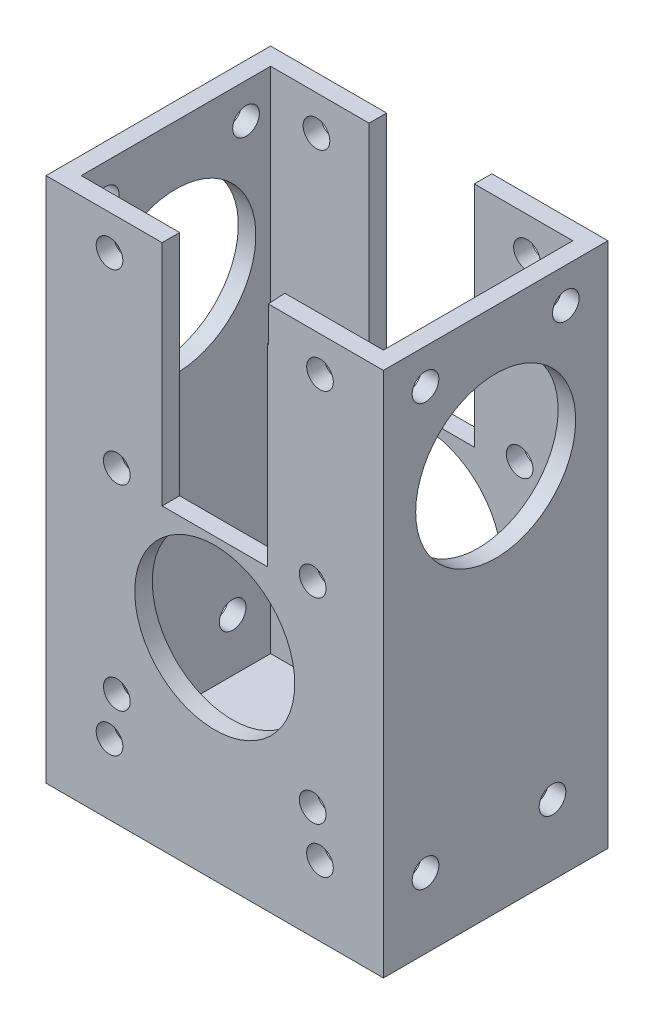
SolidWorks part; units mm, degrees
ref_plane "Front Plane" through (0, 0, 0) normal (0, 0, 1) x (1, 0, 0)
ref_plane "Top Plane" through (0, 0, 0) normal (0, 1, 0) x (1, 0, 0)
ref_plane "Right Plane" through (0, 0, 0) normal (1, 0, 0) x (0, 0, -1)
sketch "Sketch1" plane through (0, 0, 0) normal (0, 1, 0) x (1, 0, 0)
  line L1 (0, 0) -> (61.0616, 0)
  line L2 (0, 0) -> (0, 40.64)
  line L3 (0, 40.64) -> (61.0616, 40.64)
  line L4 (61.0616, 0) -> (61.0616, 40.64)
  dimension "D1" = 61.0616
  dimension "D2" = 40.64
extrude "Boss-Extrude1" add sketch "Sketch1" along normal blind 82.55
sketch "Sketch13" plane through (0, 82.55, 0) normal (0, 1, 0) x (1, 0, 0)
  line L1 (3.175, 3.175) -> (57.8866, 3.175)
  line L2 (3.175, 3.175) -> (3.175, 37.465)
  line L3 (3.175, 37.465) -> (57.8866, 37.465)
  line L4 (57.8866, 3.175) -> (57.8866, 37.465)
  dimension "D1" = 54.7116
  dimension "D2" = 34.29
extrude "Cut-Extrude1" cut sketch "Sketch13" against normal blind 82.55
sketch "Sketch15" plane through (0, 0, 0) normal (0, 0, 1) x (1, 0, 0)
  line L0 (0, 0) -> (61.0616, 0) construction
  circle A0 centre (30.5308, 31.75) radius 14.478
  dimension "D1" = 30.5308
  dimension "D2" = 31.75
extrude "Cut-Extrude2" cut sketch "Sketch15" against normal blind 3.175
sketch "Sketch16" plane through (0, 0, 0) normal (0, 0, 1) x (1, 0, 0)
  circle A0 centre (30.5308, 31.75) radius 14.478
extrude "Cut-Extrude3" cut sketch "Sketch16" against normal blind 3.175 from surface at -37.465 starting at face at (30.5308, 41.275, -37.465)
sketch "Sketch18" plane through (0, 0, 0) normal (-1, 0, 0) x (0, 0, 1)
  line L0 (-40.64, 0) -> (0, 0) construction
  line L1 (0, 82.55) -> (0, 0) construction
  circle A0 centre (-20.32, 63.754) radius 14.478
  dimension "D1" = 63.754
  dimension "D2" = 20.32
extrude "Cut-Extrude4" cut sketch "Sketch18" against normal up to vertex
sketch "Sketch19" plane through (0, 0, -40.64) normal (0, 0, -1) x (-1, 0, 0)
  line L0 (-61.0616, 82.55) -> (0, 82.55) construction
  line L1 (-40.0558, 82.55) -> (-21.0058, 82.55)
  line L2 (-40.0558, 82.55) -> (-40.0558, 47.625)
  line L3 (-40.0558, 47.625) -> (-21.0058, 47.625)
  line L4 (-21.0058, 82.55) -> (-21.0058, 47.625)
  line L5 (0, 82.55) -> (0, 0) construction
  line L6 (-61.0616, 82.55) -> (-61.0616, 0) construction
  dimension "D1" = 19.05
  dimension "D2" = 34.925
  dimension "D3" = 21.0058
  dimension "D4" = 21.0058
extrude "Cut-Extrude5" cut sketch "Sketch19" against normal up to vertex
sketch "Sketch20" plane through (0, 0, 0) normal (0, 0, 1) x (1, 0, 0)
  circle A0 centre (48.26, 14.0208) radius 2.413
  circle A1 centre (30.5308, 31.75) radius 14.478 construction
  dimension "D1" = 17.7292
  dimension "D2" = 17.7292
sketch "Sketch21" plane through (0, 0, 0) normal (0, 0, 1) x (1, 0, 0)
  circle A0 centre (48.26, 49.4737) radius 2.413
sketch "Sketch24" plane through (0, 0, 0) normal (0, 0, 1) x (1, 0, 0)
  circle A0 centre (12.8071, 49.4737) radius 2.413
sketch "Sketch25" plane through (0, 0, 0) normal (0, 0, 1) x (1, 0, 0)
  circle A0 centre (12.8071, 14.0208) radius 2.413
extrude "Cut-Extrude6" cut sketch "Sketch20" against normal up to vertex
extrude "Cut-Extrude7" cut sketch "Sketch21" against normal up to vertex
extrude "Cut-Extrude8" cut sketch "Sketch24" against normal up to vertex contours A0
extrude "Cut-Extrude9" cut sketch "Sketch25" against normal up to vertex contours A0
sketch "Sketch45" plane through (0, 0, 0) normal (0, 0, 1) x (1, 0, 0)
  line L0 (61.0616, 82.55) -> (61.0616, 0) construction
  line L1 (0, 0) -> (61.0616, 0) construction
  circle A0 centre (49.5808, 6.35) radius 2.413
  dimension "D1" = 11.4808
  dimension "D2" = 6.35
sketch "Sketch47" plane through (0, 82.55, 0) normal (0, 1, 0) x (1, 0, 0)
  line L0 (21.0058, 40.64) -> (21.0058, 37.465)
  line L1 (21.0058, 37.465) -> (3.175, 37.465)
  line L2 (3.175, 37.465) -> (3.175, 3.175)
  line L3 (3.175, 3.175) -> (21.0058, 3.175)
  line L4 (21.0058, 3.175) -> (21.0058, 0)
  line L5 (21.0058, 0) -> (0, 0)
  line L6 (0, 0) -> (0, 40.64)
  line L7 (0, 40.64) -> (20.2485, 40.64)
  line L8 (21.0058, 40.64) -> (0, 40.64) construction
  line L9 (20.2485, 40.64) -> (21.0058, 40.64)
extrude "Boss-Extrude2" add sketch "Sketch47" along normal blind 6.35
sketch "Sketch49" plane through (0, 82.55, 0) normal (0, 1, 0) x (1, 0, 0)
  line L0 (40.0558, 37.465) -> (40.0558, 40.64)
  line L1 (40.0558, 40.64) -> (61.0616, 40.64)
  line L2 (61.0616, 40.64) -> (61.0616, 0)
  line L3 (61.0616, 0) -> (40.2245, 0)
  line L4 (40.2245, 0) -> (40.0558, 3.175)
  line L5 (40.0558, 3.175) -> (57.8866, 3.175)
  line L6 (57.8866, 3.175) -> (57.8866, 37.465)
  line L7 (57.8866, 37.465) -> (40.0558, 37.465)
extrude "Boss-Extrude3" add sketch "Sketch49" along normal blind 6.35
sketch "Sketch53" plane through (0, 0, 0) normal (0, -1, 0) x (1, 0, 0)
  line L1 (0, 0) -> (61.0616, 0)
  line L2 (0, 0) -> (0, -40.64)
  line L3 (0, -40.64) -> (61.0616, -40.64)
  line L4 (61.0616, 0) -> (61.0616, -40.64)
  line L5 (3.175, -3.175) -> (57.8866, -3.175)
  line L6 (3.175, -3.175) -> (3.175, -37.465)
  line L7 (3.175, -37.465) -> (57.8866, -37.465)
  line L8 (57.8866, -3.175) -> (57.8866, -37.465)
extrude "Boss-Extrude5" add sketch "Sketch53" along normal blind 3.175
sketch "Sketch54" plane through (0, -3.175, 0) normal (0, -1, 0) x (1, 0, 0)
  line L1 (0, 0) -> (61.0616, 0)
  line L2 (0, 0) -> (0, -40.64)
  line L3 (0, -40.64) -> (61.0616, -40.64)
  line L4 (61.0616, 0) -> (61.0616, -40.64)
extrude "Boss-Extrude6" add sketch "Sketch54" along normal blind 3.175
extrude "Cut-Extrude14" cut sketch "Sketch45" against normal up to vertex
sketch "Sketch59" plane through (0, 0, 0) normal (0, 0, 1) x (1, 0, 0)
  circle A0 centre (49.5808, 82.55) radius 2.413
  circle A1 centre (49.5808, 6.35) radius 2.413 construction
  dimension "D1" = 76.2
extrude "Cut-Extrude18" cut sketch "Sketch59" against normal up to vertex contours A0
sketch "Sketch60" plane through (0, 0, 0) normal (0, 0, 1) x (1, 0, 0)
  circle A0 centre (11.4808, 6.35) radius 2.413
  circle A1 centre (49.5808, 6.35) radius 2.413 construction
  dimension "D1" = 38.1
extrude "Cut-Extrude19" cut sketch "Sketch60" against normal up to vertex
sketch "Sketch61" plane through (0, 0, 0) normal (0, 0, 1) x (1, 0, 0)
  circle A0 centre (11.4808, 82.55) radius 2.413
extrude "Cut-Extrude20" cut sketch "Sketch61" against normal up to vertex
sketch "Sketch63" plane through (0, 0, 0) normal (-1, 0, 0) x (0, 0, 1)
  line L0 (-40.64, 88.9) -> (-40.64, -6.35) construction
  line L1 (-40.64, 88.9) -> (0, 88.9) construction
  circle A0 centre (-33.02, 82.55) radius 2.413
  dimension "D1" = 7.62
  dimension "D2" = 6.35
extrude "Cut-Extrude21" cut sketch "Sketch63" against normal up to vertex
sketch "Sketch64" plane through (0, 0, 0) normal (-1, 0, 0) x (0, 0, 1)
  circle A0 centre (-7.62, 82.55) radius 2.413
  circle A1 centre (-33.02, 82.55) radius 2.413 construction
  dimension "D1" = 25.4
extrude "Cut-Extrude22" cut sketch "Sketch64" against normal up to vertex
sketch "Sketch65" plane through (0, 0, 0) normal (-1, 0, 0) x (0, 0, 1)
  circle A0 centre (-30.607, 6.35) radius 2.413
  circle A1 centre (-33.02, 82.55) radius 2.413 construction
  dimension "D1" = 76.2
extrude "Cut-Extrude23" cut sketch "Sketch65" against normal up to vertex
sketch "Sketch66" plane through (0, 0, 0) normal (-1, 0, 0) x (0, 0, 1)
  circle A0 centre (-7.62, 6.35) radius 2.413
extrude "Cut-Extrude24" cut sketch "Sketch66" against normal up to vertex
